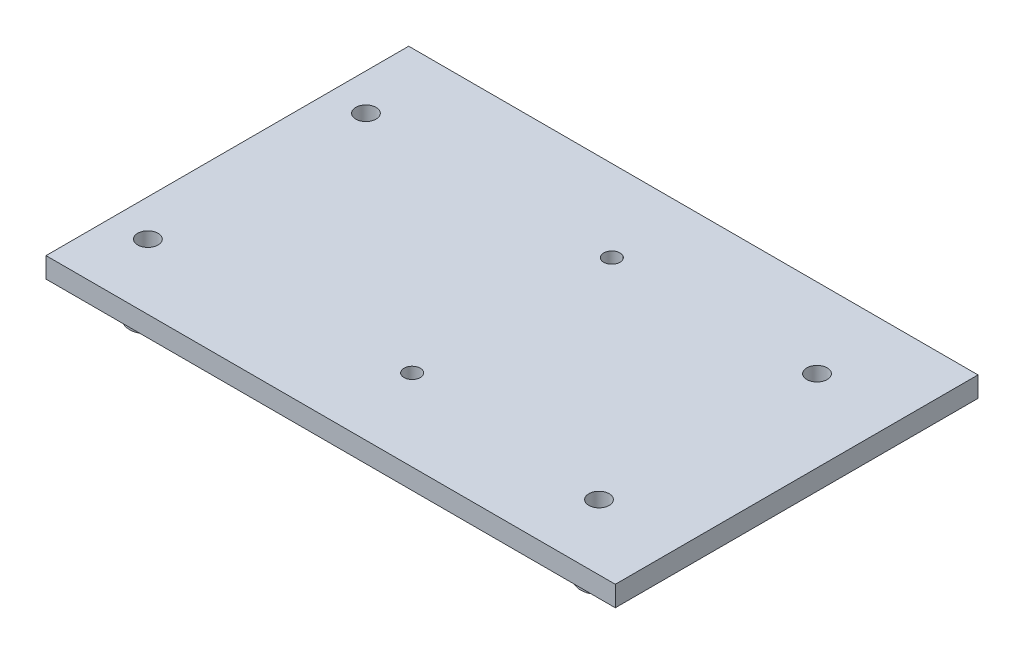
SolidWorks part; units mm, degrees
ref_plane "Front Plane" through (0, 0, 0) normal (0, 0, 1) x (1, 0, 0)
ref_plane "Top Plane" through (0, 0, 0) normal (0, 1, 0) x (1, 0, 0)
ref_plane "Right Plane" through (0, 0, 0) normal (1, 0, 0) x (0, 0, -1)
other "Bounding Box"
ref_plane "Default Plane" through (-70.0319, 5, -44.8637) normal (0, 0, 1) x (1, 0, 0)
sketch "Sketch1" plane through (0, 0, 0) normal (0, 1, 0) x (1, 0, 0)
  line L0 (-70.0319, -44.1363) -> (69.6681, -44.1363)
  line L1 (-70.0319, -44.1363) -> (-70.0319, 44.8637)
  line L2 (-70.0319, 44.8637) -> (69.6681, 44.8637)
  line L3 (69.6681, -44.1363) -> (69.6681, 44.8637)
  point P4 (-65.4319, -39.3363)
  point P5 (-65.4319, 40.2637)
  point P6 (46.6681, 38.7637)
  point P7 (46.6681, -39.3363)
  dimension "D1" = 139.7
extrude "Boss-Extrude1" add sketch "Sketch1" along normal blind 5
sketch "Sketch4" plane through (0, 0, 0) normal (0, -1, 0) x (1, 0, 0)
  line L0 (69.6681, -44.8637) -> (-70.0319, -44.8637) construction
  line L1 (-70.0319, 44.1363) -> (69.6681, 44.1363) construction
  line L2 (-61.0319, 28.1363) -> (70.0963, 28.1363) construction
  line L3 (-70.0319, -44.8637) -> (-70.0319, 44.1363) construction
  line L4 (69.6681, 44.1363) -> (69.6681, -44.8637) construction
  line L5 (-61.0319, 28.1363) -> (-61.0319, -53.7767) construction
  line L6 (49.6681, 28.1363) -> (49.6681, -56.2903) construction
  circle A8 centre (-61.0319, 28.1363) radius 2.5
  circle A9 centre (49.6681, 28.1363) radius 2.5
  circle A10 centre (-61.0319, -25.3637) radius 2.5
  circle A11 centre (49.6681, -25.3637) radius 2.5
  circle A12 centre (-61.0319, 28.1363) radius 4.5
  circle A13 centre (49.6681, 28.1363) radius 4.5
  circle A14 centre (-61.0319, -25.3637) radius 4.5
  circle A15 centre (49.6681, -25.3637) radius 4.5
  dimension "D1" = 16
  dimension "D2" = 5
  dimension "D3" = 5
  dimension "D6" = 5
  dimension "D7" = 19.5
  dimension "D8" = 5
  dimension "D9" = 9
  dimension "D10" = 9
  dimension "D11" = 9
  dimension "D12" = 9
  dimension "D4" = 9
  dimension "D5" = 20
extrude "Boss-Extrude2" add sketch "Sketch4" along normal blind 12
sketch "Sketch12" plane through (0, 0, 0) normal (0, -1, 0) x (1, 0, 0)
  line L0 (-70.0319, 44.1363) -> (69.6681, 44.1363) construction
  line L1 (-70.0319, -44.8637) -> (69.6681, -44.8637) construction
  circle A0 centre (-0.1819, 24.1363) radius 2
  circle A1 centre (-0.1819, -24.8637) radius 2
  point P0 (-0.1819, 44.1363)
  point P1 (-0.1819, -44.8637)
  point P4 (-0.1819, -24.8637)
  point P10 (-0.1819, 24.1363)
  dimension "D1" = 20
  dimension "D2" = 20
extrude "Cut-Extrude1" cut sketch "Sketch12" against normal blind 5
sketch "Sketch13" plane through (0, 0, 0) normal (0, -1, 0) x (1, 0, 0)
  circle A4 centre (-61.0319, 28.1363) radius 2.5
  circle A5 centre (-61.0319, -25.3637) radius 2.5
  circle A6 centre (49.6681, -25.3637) radius 2.5
  circle A7 centre (49.6681, 28.1363) radius 2.5
extrude "Cut-Extrude2" cut sketch "Sketch13" against normal blind 10
